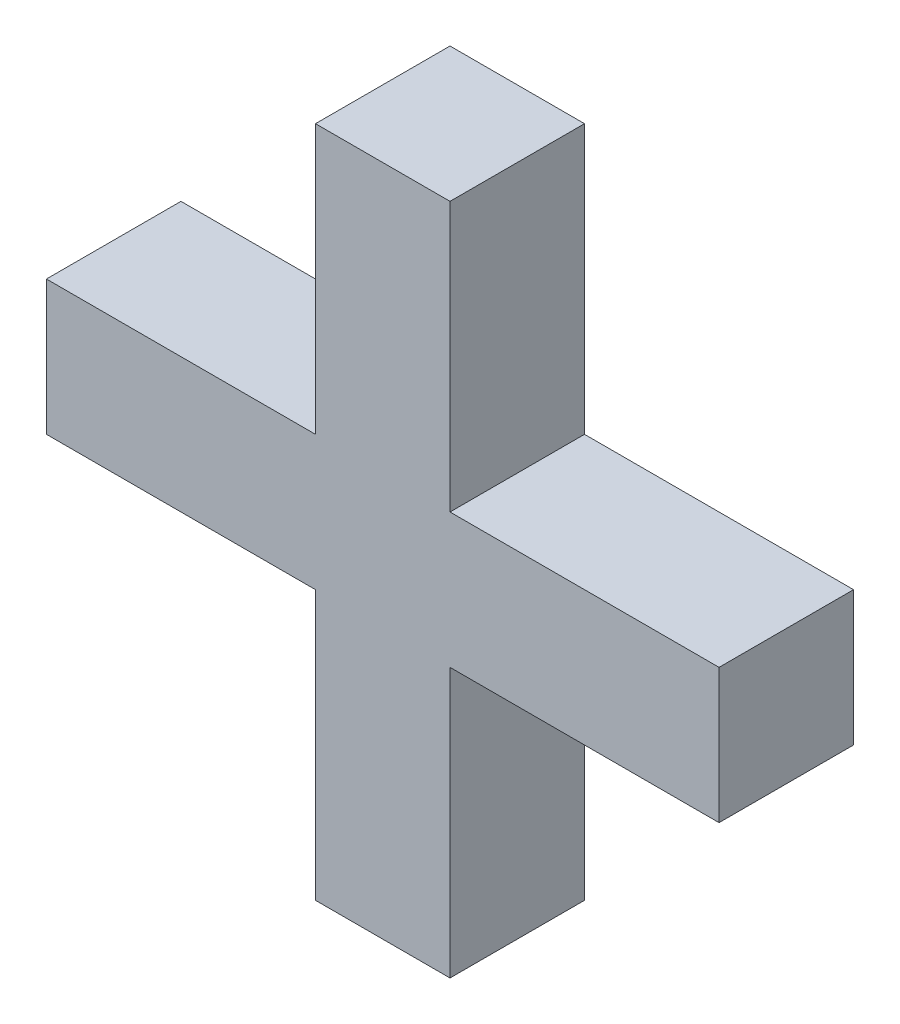
SolidWorks part; units mm, degrees
ref_plane "Front Plane" through (0, 0, 0) normal (0, 0, 1) x (1, 0, 0)
ref_plane "Top Plane" through (0, 0, 0) normal (0, 1, 0) x (1, 0, 0)
ref_plane "Right Plane" through (0, 0, 0) normal (1, 0, 0) x (0, 0, -1)
sketch "Sketch1" plane through (0, 0, 0) normal (0, 0, 1) x (1, 0, 0)
  line L1 (0, 0) -> (1, 0)
  line L2 (0, 0) -> (0, -5)
  line L3 (0, -5) -> (1, -5)
  line L4 (1, 0) -> (1, -5)
  dimension "D1" = 1
  dimension "D2" = 5
extrude "Boss-Extrude1" add sketch "Sketch1" along normal blind 1
sketch "Sketch2" plane through (1, 0, 0) normal (1, 0, 0) x (0, 0, -1)
  line L0 (-1, 0) -> (0, -5)
  circle A0 centre (-0.5, -2.5) radius 0.2289
extrude "Boss-Extrude2" add sketch "Sketch2" along normal blind 0.01 contours A0
sketch "Sketch3" plane through (0, 0, 0) normal (-1, 0, 0) x (0, 0, 1)
  line L0 (0, -5) -> (1, 0)
  line L2 (1, -3) -> (0, -3)
  line L3 (1, -3) -> (1, -2)
  line L4 (1, -2) -> (0, -2)
  line L5 (0, -3) -> (0, -2)
  line L6 (1, -3) -> (0, -2) construction
  line L7 (1, -2) -> (0, -3) construction
  point P4 (0.5, -2.5)
  line M2 (0, 0) -> (0, -5)
  line M4 (1, -5) -> (1, 0)
extrude "Boss-Extrude3" add sketch "Sketch3" along normal blind 2 and the other way blind 3 contours L4 L0 L2 M4 | L0 L4 L2 M2
